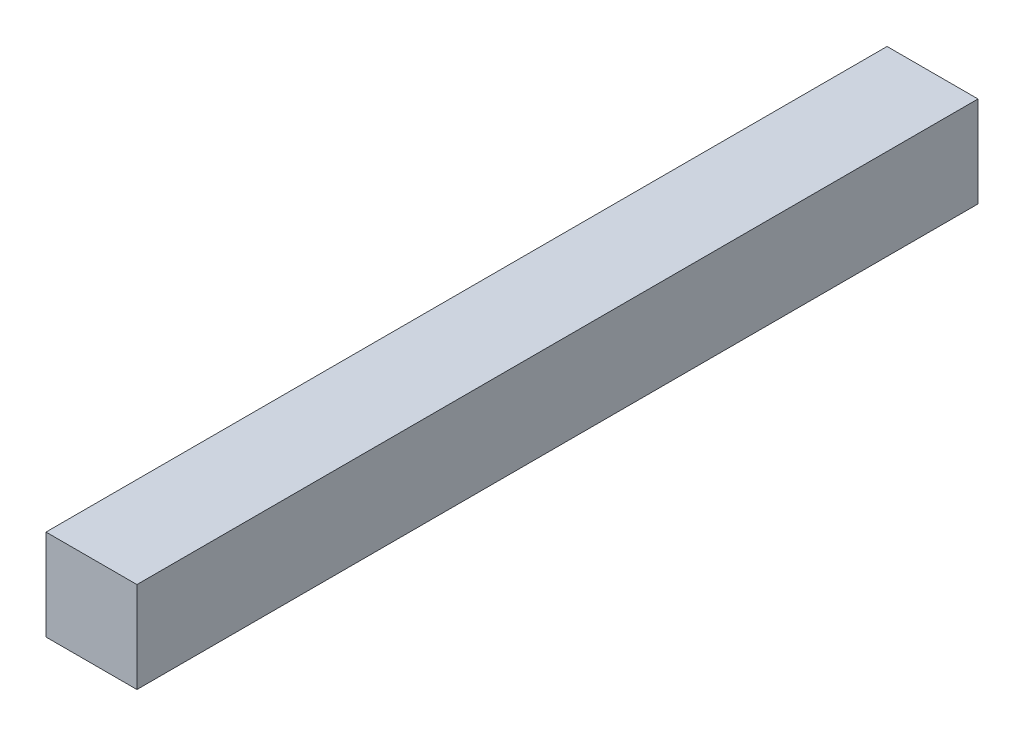
SolidWorks part; units mm, degrees
ref_plane "Front Plane" through (0, 0, 0) normal (0, 0, 1) x (1, 0, 0)
ref_plane "Top Plane" through (0, 0, 0) normal (0, 1, 0) x (1, 0, 0)
ref_plane "Right Plane" through (0, 0, 0) normal (1, 0, 0) x (0, 0, -1)
sketch "Sketch1" plane through (0, 0, 0) normal (1, 0, 0) x (0, 0, -1)
  line L0 (126.5431, 0) -> (-135.6999, 0) construction
  line L1 (0, 105.7009) -> (0, -97.8505) construction
  line L3 (-92.5, 10) -> (92.5, 10)
  line L4 (-92.5, 10) -> (-92.5, -10)
  line L5 (-92.5, -10) -> (92.5, -10)
  line L6 (92.5, 10) -> (92.5, -10)
  point P9 (92.5, 0)
  point P10 (0, 10)
  dimension "D1" = 20
  dimension "D2" = 185
extrude "Boss-Extrude1" add sketch "Sketch1" along normal blind 20
sketch "Sketch2" plane through (0, 0, 0) normal (1, 0, 0) x (0, 0, -1)
  line L0 (-92.5, 0) -> (92.5, 0) construction
  line L1 (0, 22.843) -> (0, -26.6092) construction
  line L2 (-92.5, 10) -> (-92.5, -10) construction
  line L3 (-92.5, 10) -> (-92.5, -10) construction
  line L4 (92.5, -10) -> (92.5, 10) construction
  line L5 (92.5, -10) -> (92.5, 10) construction
  text T0 "height" font "Century Gothic" height in points 20
extrude "Cut-Extrude1" cut sketch "Sketch2" along normal blind 4
